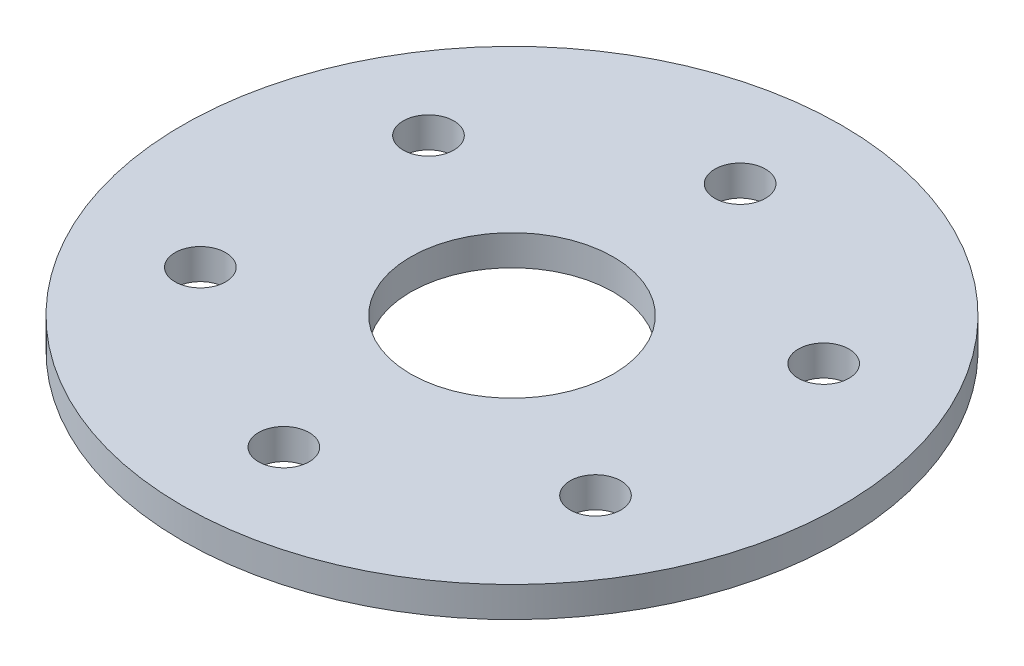
SolidWorks part; units mm, degrees
ref_plane "前视基准面" through (0, 0, 0) normal (0, 0, 1) x (1, 0, 0)
ref_plane "上视基准面" through (0, 0, 0) normal (0, 1, 0) x (1, 0, 0)
ref_plane "右视基准面" through (0, 0, 0) normal (1, 0, 0) x (0, 0, -1)
other "Configuration Table"
sketch "草图1" plane through (0, 0, 0) normal (0, 1, 0) x (1, 0, 0)
  circle A0 centre (0, 0) radius 32.5
  circle A1 centre (0, 0) radius 10
  dimension "D1" = 20
  dimension "D2" = 65
extrude "凸台-拉伸1" add sketch "草图1" along normal blind 3
sketch "草图2" plane through (0, 3, 0) normal (0, 1, 0) x (1, 0, 0)
  circle A0 centre (0, 0) radius 22.5 construction
  circle A1 centre (0, 22.5) radius 2.5
  circle A2 centre (19.4856, 11.25) radius 2.5
  circle A3 centre (19.4856, -11.25) radius 2.5
  circle A4 centre (0, -22.5) radius 2.5
  circle A5 centre (-19.4856, -11.25) radius 2.5
  circle A6 centre (-19.4856, 11.25) radius 2.5
  point P5 (-22.6743, 7.5737)
  point P6 (0, 0)
  point P18 (0, 0)
  dimension "D1" = 45
  dimension "D2" = 5
  dimension "D3" = 6
extrude "切除-拉伸1" cut sketch "草图2" against normal blind 3
